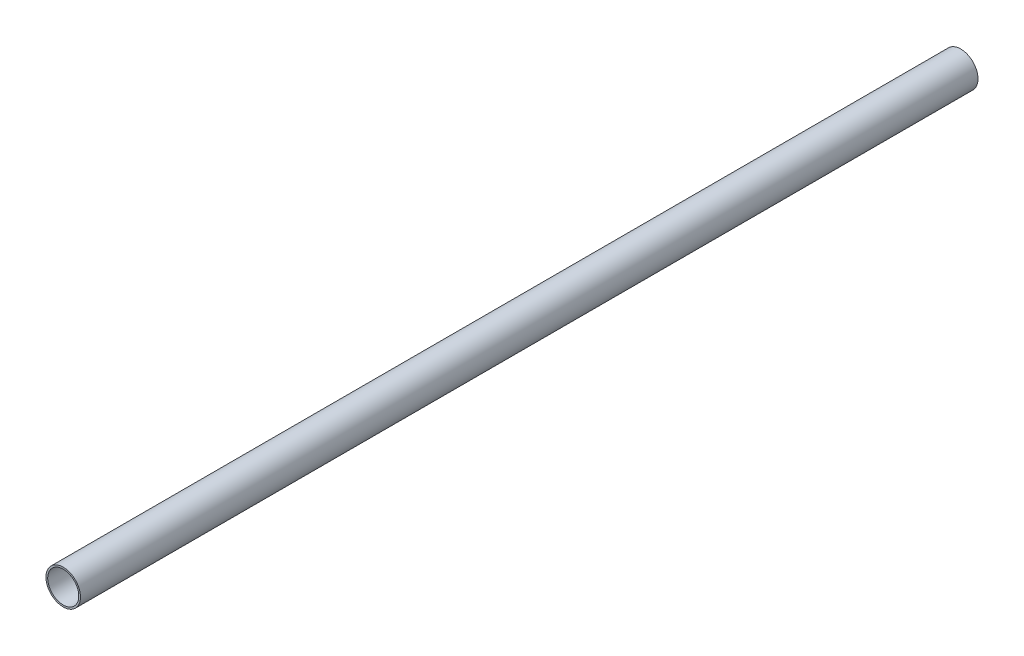
SolidWorks part; units mm, degrees
material "Carbon Fiber Tube - UD Approx"
ref_plane "Front Plane" through (0, 0, 0) normal (0, 0, 1) x (1, 0, 0)
ref_plane "Top Plane" through (0, 0, 0) normal (0, 1, 0) x (1, 0, 0)
ref_plane "Right Plane" through (0, 0, 0) normal (1, 0, 0) x (0, 0, -1)
sketch "Sketch1" plane through (0, 0, 0) normal (0, 0, 1) x (1, 0, 0)
  circle A0 centre (0, 0) radius 10
  circle A1 centre (0, 0) radius 9
  dimension "D1" = 20
  dimension "D2" = 18
extrude "Boss-Extrude1" add sketch "Sketch1" along normal blind 520
